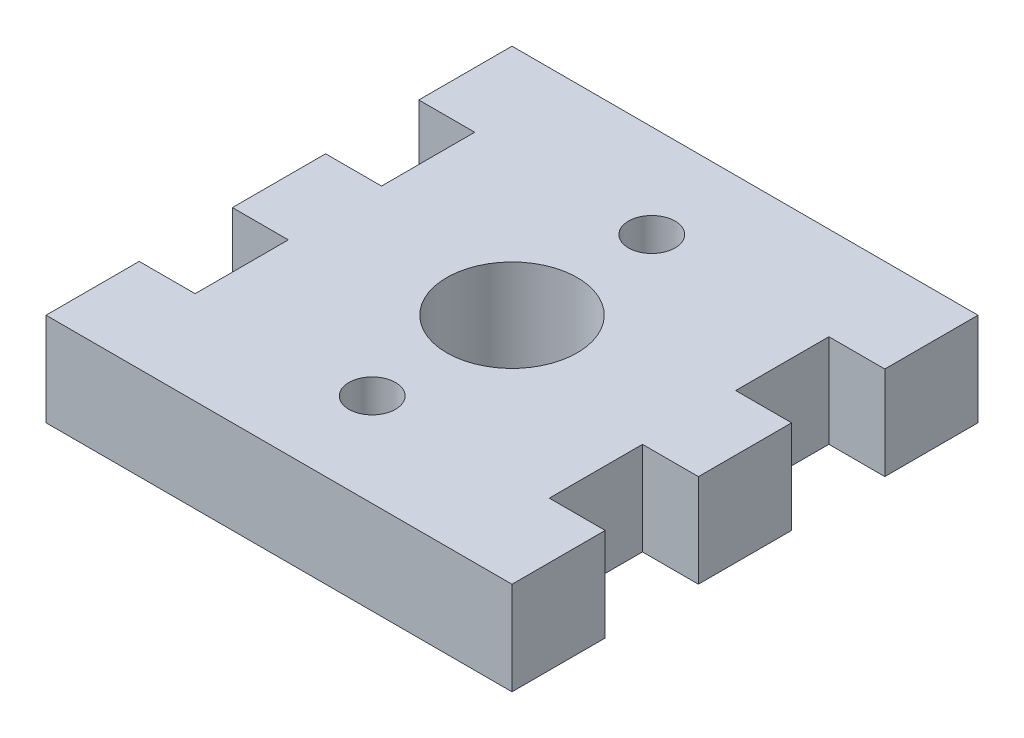
SolidWorks part; units mm, degrees
ref_plane "Front Plane" through (0, 0, 0) normal (0, 0, 1) x (1, 0, 0)
ref_plane "Top Plane" through (0, 0, 0) normal (0, 1, 0) x (1, 0, 0)
ref_plane "Right Plane" through (0, 0, 0) normal (1, 0, 0) x (0, 0, -1)
sketch "Sketch1" plane through (0, 0, 0) normal (0, 1, 0) x (1, 0, 0)
  line L1 (-11.157, -14.3595) -> (13.843, -14.3595)
  line L2 (-11.157, -14.3595) -> (-11.157, 10.6405)
  line L3 (-11.157, 10.6405) -> (13.843, 10.6405)
  line L4 (13.843, -14.3595) -> (13.843, 10.6405)
  circle A0 centre (1.343, -1.8595) radius 3.5
  point P8 (-8.9975, 1.8651)
  dimension "D5" = 7
  dimension "D1" = 25
  dimension "D2" = 25
  dimension "D3" = 12.5
  dimension "D4" = 12.5
extrude "Boss-Extrude1" add sketch "Sketch1" along normal blind 5
sketch "Sketch2" plane through (0, 5, 0) normal (0, 1, 0) x (1, 0, 0)
  line L0 (-11.157, 10.6405) -> (-11.157, -14.3595) construction
  line L1 (-11.157, 5.6405) -> (-8.157, 5.6405)
  line L2 (-11.157, 5.6405) -> (-11.157, 0.6405)
  line L3 (-11.157, 0.6405) -> (-8.157, 0.6405)
  line L4 (-8.157, 5.6405) -> (-8.157, 0.6405)
  line L5 (13.843, 10.6405) -> (-11.157, 10.6405) construction
  line L8 (-11.157, -1.8595) -> (13.843, -1.8595) construction
  line L9 (13.843, -14.3595) -> (13.843, 10.6405) construction
  line L10 (1.343, 10.6405) -> (1.343, -14.3595) construction
  line L11 (-11.157, -14.3595) -> (13.843, -14.3595) construction
  line L12 (-11.157, -4.3595) -> (-8.157, -4.3595)
  line L13 (-8.157, -9.3595) -> (-8.157, -4.3595)
  line L14 (-11.157, -9.3595) -> (-8.157, -9.3595)
  line L15 (-11.157, -9.3595) -> (-11.157, -4.3595)
  line L16 (13.843, -9.3595) -> (13.843, -4.3595)
  line L17 (13.843, -9.3595) -> (10.843, -9.3595)
  line L18 (10.843, -9.3595) -> (10.843, -4.3595)
  line L19 (13.843, -4.3595) -> (10.843, -4.3595)
  line L20 (13.843, 0.6405) -> (10.843, 0.6405)
  line L21 (10.843, 5.6405) -> (10.843, 0.6405)
  line L22 (13.843, 5.6405) -> (10.843, 5.6405)
  line L23 (13.843, 5.6405) -> (13.843, 0.6405)
  line L25 (-6.157, 10.6405) -> (-1.157, 10.6405)
  line L26 (-6.157, 10.6405) -> (-6.157, 7.6405)
  line L27 (-6.157, 7.6405) -> (-1.157, 7.6405)
  line L28 (-1.157, 10.6405) -> (-1.157, 7.6405)
  dimension "D1" = 3
  dimension "D2" = 5
  dimension "D3" = 5
  dimension "D4" = 5
  dimension "D5" = 3
  dimension "D6" = 5
extrude "Cut-Extrude1" cut sketch "Sketch2" against normal blind 15 contours L2 L1 L4 L3 | L12 L13 L14 L15 | L16 L19 L18 L17 | L20 L21 L22 L23
sketch "Sketch3" plane through (0, 5, 0) normal (0, 1, 0) x (1, 0, 0)
  circle A0 centre (1.343, 5.6405) radius 1.25
  circle A1 centre (1.343, -9.3595) radius 1.25
  circle A2 centre (1.343, -1.8595) radius 3.4023
  circle A3 centre (1.343, -1.8595) radius 3.5 construction
  point P8 (5.4389, -9.3595)
  dimension "D3" = 2.5
  dimension "D5" = 2.5
  dimension "D6" = 0
  dimension "D1" = 7.5
  dimension "D2" = 0
  dimension "D4" = 7.5
extrude "Cut-Extrude2" cut sketch "Sketch3" against normal blind 5
